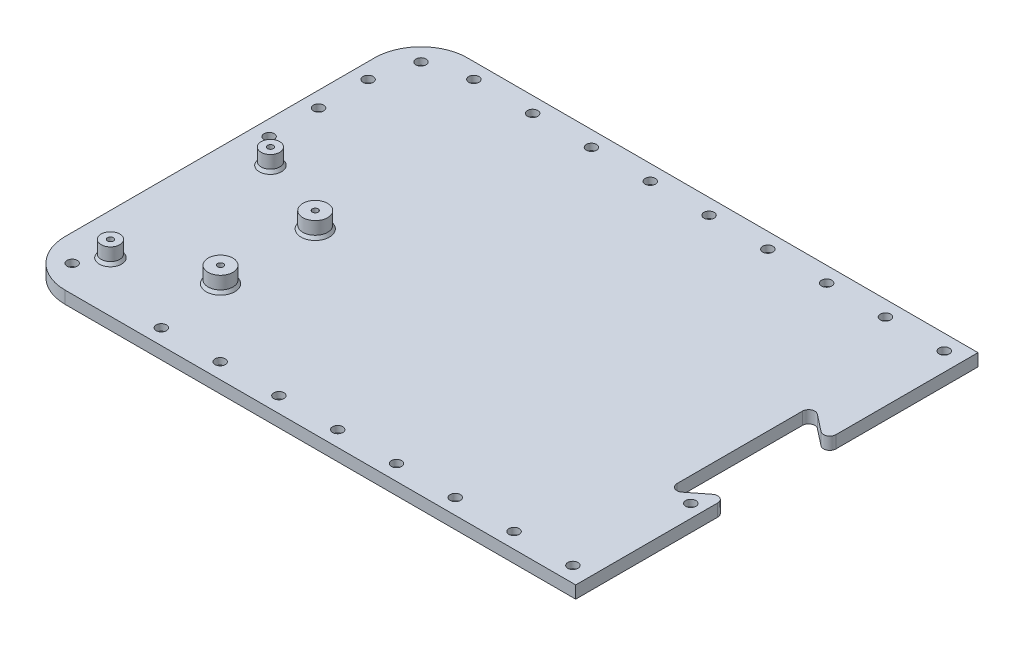
SolidWorks part; units mm, degrees
ref_plane "前视基准面" through (0, 0, 0) normal (0, 0, 1) x (1, 0, 0)
ref_plane "上视基准面" through (0, 0, 0) normal (0, 1, 0) x (1, 0, 0)
ref_plane "右视基准面" through (0, 0, 0) normal (1, 0, 0) x (0, 0, -1)
sketch "草图1" plane through (0, 0, 0) normal (0, 1, 0) x (1, 0, 0)
  line L12 (73.8085, -15.6287) -> (68.2711, -19.955)
  line L13 (77.0398, -63.1041) -> (77.0398, -17.2047)
  line L14 (-87.9602, -63.1041) -> (77.0398, -63.1041)
  line L15 (-102.9602, 51.8959) -> (-102.9602, -48.1041)
  line L16 (77.0398, 66.8959) -> (-87.9602, 66.8959)
  line L17 (77.0398, 20.9965) -> (77.0398, 66.8959)
  line L18 (68.2711, 23.7467) -> (73.8085, 19.4205)
  line L19 (65.0398, -18.379) -> (65.0398, 22.1707)
  line L20 (73.8085, -15.6287) -> (68.2711, -19.955)
  line L21 (77.0398, -63.1041) -> (77.0398, -17.2047)
  line L22 (-87.9602, -63.1041) -> (77.0398, -63.1041)
  line L23 (-102.9602, 51.8959) -> (-102.9602, -48.1041)
  line L24 (77.0398, 66.8959) -> (-87.9602, 66.8959)
  line L25 (77.0398, 20.9965) -> (77.0398, 66.8959)
  line L26 (68.2711, 23.7467) -> (73.8085, 19.4205)
  line L27 (65.0398, -18.379) -> (65.0398, 22.1707)
  arc A6 (77.0398, -17.2047) -> (73.8085, -15.6287) centre (75.0398, -17.2047) ccw
  arc A7 (-102.9602, -48.1041) -> (-87.9602, -63.1041) centre (-87.9602, -48.1041) ccw
  arc A8 (-87.9602, 66.8959) -> (-102.9602, 51.8959) centre (-87.9602, 51.8959) ccw
  arc A9 (73.8085, 19.4205) -> (77.0398, 20.9965) centre (75.0398, 20.9965) ccw
  arc A10 (68.2711, 23.7467) -> (65.0398, 22.1707) centre (67.0398, 22.1707) ccw
  arc A11 (65.0398, -18.379) -> (68.2711, -19.955) centre (67.0398, -18.379) ccw
  arc A12 (77.0398, -17.2047) -> (73.8085, -15.6287) centre (75.0398, -17.2047) ccw
  arc A13 (-102.9602, -48.1041) -> (-87.9602, -63.1041) centre (-87.9602, -48.1041) ccw
  arc A14 (-87.9602, 66.8959) -> (-102.9602, 51.8959) centre (-87.9602, 51.8959) ccw
  arc A15 (73.8085, 19.4205) -> (77.0398, 20.9965) centre (75.0398, 20.9965) ccw
  arc A16 (68.2711, 23.7467) -> (65.0398, 22.1707) centre (67.0398, 22.1707) ccw
  arc A17 (65.0398, -18.379) -> (68.2711, -19.955) centre (67.0398, -18.379) ccw
  point P0 (0, 0)
  dimension "D1" = 0
extrude "凸台-拉伸1" add sketch "草图1" along normal blind 4
sketch "草图2" plane through (0, 4, 0) normal (0, 1, 0) x (1, 0, 0)
  circle A0 centre (72.8398, -21.7154) radius 1.65 construction
  circle A1 centre (71.1252, -58.1041) radius 1.65 construction
  circle A2 centre (52.1252, -58.1041) radius 1.65 construction
  circle A3 centre (33.1252, -58.1041) radius 1.65 construction
  circle A4 centre (14.1252, -58.1041) radius 1.65 construction
  circle A5 centre (-4.8748, -58.1041) radius 1.65 construction
  circle A6 centre (-23.8748, -58.1041) radius 1.65 construction
  circle A7 centre (-42.8748, -58.1041) radius 1.65 construction
  circle A8 centre (-61.8748, -58.1041) radius 1.65 construction
  circle A9 centre (-94.3241, -54.4681) radius 1.65 construction
  circle A10 centre (-97.9602, 12.8105) radius 1.65 construction
  circle A11 centre (-97.9602, 28.8105) radius 1.65 construction
  circle A12 centre (-97.9602, 44.8105) radius 1.65 construction
  circle A13 centre (-94.3241, 58.2598) radius 1.65 construction
  circle A15 centre (52.1252, 61.8959) radius 1.65 construction
  circle A16 centre (33.1252, 61.8959) radius 1.65 construction
  circle A17 centre (14.1252, 61.8959) radius 1.65 construction
  circle A18 centre (-4.8748, 61.8959) radius 1.65 construction
  circle A19 centre (-23.8748, 61.8959) radius 1.65 construction
  circle A20 centre (-42.8748, 61.8959) radius 1.65 construction
  circle A21 centre (-61.8748, 61.8959) radius 1.65 construction
  circle A22 centre (-80.8748, 61.8959) radius 1.65 construction
  circle A23 centre (72.8398, -21.7154) radius 1.65
  circle A24 centre (71.1252, -58.1041) radius 1.65
  circle A25 centre (52.1252, -58.1041) radius 1.65
  circle A26 centre (33.1252, -58.1041) radius 1.65
  circle A27 centre (14.1252, -58.1041) radius 1.65
  circle A28 centre (-4.8748, -58.1041) radius 1.65
  circle A29 centre (-23.8748, -58.1041) radius 1.65
  circle A30 centre (-42.8748, -58.1041) radius 1.65
  circle A31 centre (-61.8748, -58.1041) radius 1.65
  circle A32 centre (-94.3241, -54.4681) radius 1.65
  circle A33 centre (-97.9602, 12.8105) radius 1.65
  circle A34 centre (-97.9602, 28.8105) radius 1.65
  circle A35 centre (-97.9602, 44.8105) radius 1.65
  circle A36 centre (-94.3241, 58.2598) radius 1.65
  circle A37 centre (71.1252, 61.8959) radius 1.65
  circle A38 centre (52.1252, 61.8959) radius 1.65
  circle A39 centre (33.1252, 61.8959) radius 1.65
  circle A40 centre (14.1252, 61.8959) radius 1.65
  circle A41 centre (-4.8748, 61.8959) radius 1.65
  circle A42 centre (-23.8748, 61.8959) radius 1.65
  circle A43 centre (-42.8748, 61.8959) radius 1.65
  circle A44 centre (-61.8748, 61.8959) radius 1.65
  circle A45 centre (-80.8748, 61.8959) radius 1.65
extrude "切除-拉伸1" cut sketch "草图2" against normal blind 2.1
sketch "草图3" plane through (0, 4, 0) normal (0, 1, 0) x (1, 0, 0)
  circle A0 centre (-89.6939, 4.9863) radius 3
  circle A1 centre (-89.6939, -46.7198) radius 3
  circle A2 centre (-64.6748, -36.1718) radius 4
  circle A3 centre (-64.6748, -5.5617) radius 4
  dimension "D1" = 6
  dimension "D2" = 8
  dimension "D3" = 8
  dimension "D4" = 6
extrude "凸台-拉伸2" add sketch "草图3" along normal offset from surface (5.1499 mm away) 0.15
sketch "草图4" plane through (0, 9.1499, 0) normal (0, 1, 0) x (1, 0, 0)
  circle A0 centre (-89.6939, -46.7198) radius 0.95
  circle A1 centre (-64.6748, -36.1718) radius 0.95
  circle A2 centre (-64.6748, -5.5617) radius 0.95
  circle A3 centre (-89.6939, 4.9863) radius 0.95
  dimension "D1" = 1.9
  dimension "D2" = 1.9
  dimension "D3" = 1.9
  dimension "D4" = 1.9
extrude "切除-拉伸2" cut sketch "草图4" against normal blind 5
chamfer "倒角1" distance 0.6 angle 60 4 edges at (-89.6939, 4, -1.9863) (-64.6748, 4, 9.5617) (-89.6939, 4, 49.7198) (-64.6748, 4, 40.1718)
